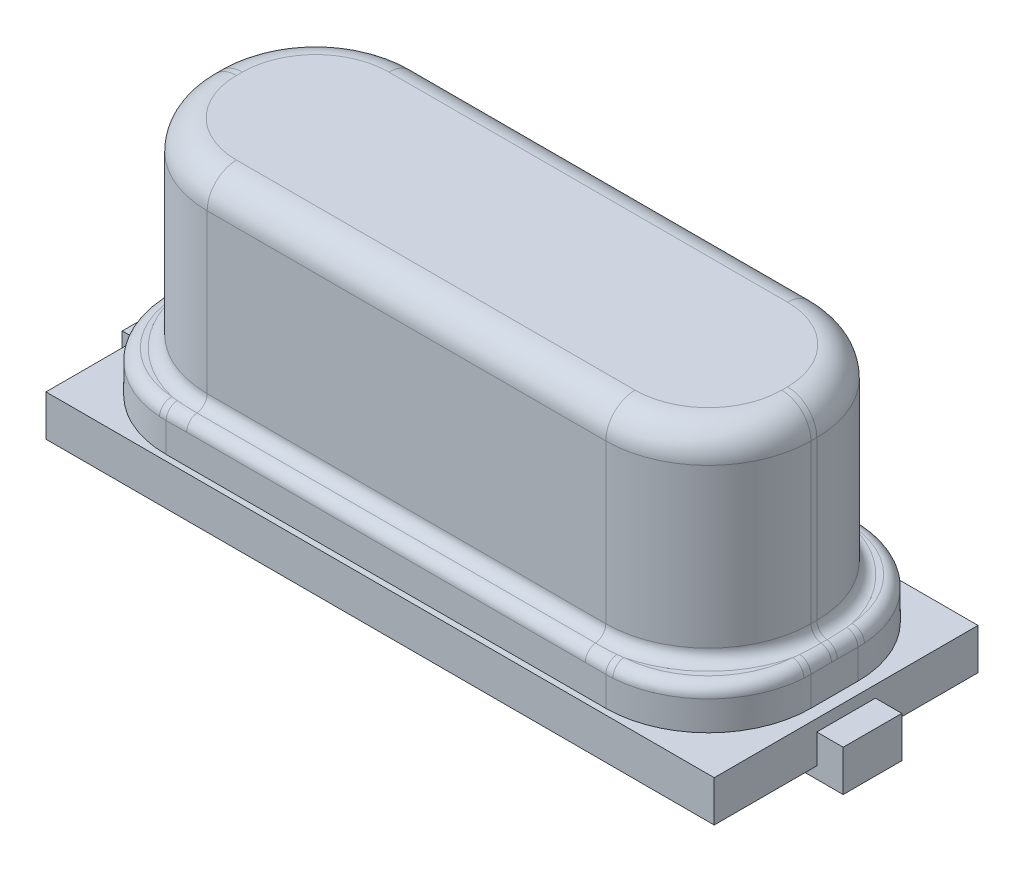
SolidWorks part; units mm, degrees
ref_plane "Спереди" through (0, 0, 0) normal (0, 0, 1) x (1, 0, 0)
ref_plane "Сверху" through (0, 0, 0) normal (0, 1, 0) x (1, 0, 0)
ref_plane "Справа" through (0, 0, 0) normal (1, 0, 0) x (0, 0, -1)
sketch "Эскиз1" plane through (0, 0, 0) normal (0, 1, 0) x (1, 0, 0)
  line L0 (-6.15, 0) -> (6.15, 0) construction
  line L1 (0, 2.25) -> (0, -2.25) construction
  line L2 (-6.15, 0.5) -> (-6.15, -0.5) construction
  line L4 (-6.15, 0.5) -> (-3, 0.5)
  line L5 (-6.15, 0.5) -> (-6.15, -0.5)
  line L6 (-6.15, -0.5) -> (-3, -0.5)
  line L7 (-3, 0.5) -> (-3, -0.5)
  line L8 (6.15, 0.5) -> (3, 0.5)
  line L9 (6.15, 0.5) -> (6.15, -0.5)
  line L10 (6.15, -0.5) -> (3, -0.5)
  line L11 (3, 0.5) -> (3, -0.5)
extrude "Бобышка-Вытянуть1" add sketch "Эскиз1" along normal blind 0.7
ref_plane "Плоскость1" through (0, 0.2, 0) normal (0, -1, 0) x (-1, 0, 0)
sketch "Эскиз6" plane through (0, 0.2, 0) normal (0, -1, 0) x (-1, 0, 0)
  line L1 (5.7, 2.25) -> (-5.7, 2.25)
  line L2 (5.7, 2.25) -> (5.7, -2.25)
  line L3 (5.7, -2.25) -> (-5.7, -2.25)
  line L4 (-5.7, 2.25) -> (-5.7, -2.25)
  line L5 (5.7, 2.25) -> (-5.7, -2.25) construction
  line L6 (5.7, -2.25) -> (-5.7, 2.25) construction
  point P0 (0, 0)
extrude "Бобышка-Вытянуть4" add sketch "Эскиз6" against normal blind 0.7
sketch "Эскиз7" plane through (0, 0.9, 0) normal (0, 1, 0) x (1, 0, 0)
  line L1 (-3.75, 2.15) -> (3.75, 2.15)
  line L2 (-5.5, 0.4) -> (-5.5, -0.4)
  line L3 (-3.75, -2.15) -> (3.75, -2.15)
  line L4 (5.5, 0.4) -> (5.5, -0.4)
  line L5 (-5.5, 2.15) -> (5.5, -2.15) construction
  line L6 (-5.5, -2.15) -> (5.5, 2.15) construction
  arc A0 (3.75, 2.15) -> (5.5, 0.4) centre (3.75, 0.4) cw
  arc A1 (3.75, -2.15) -> (5.5, -0.4) centre (3.75, -0.4) ccw
  arc A2 (-5.5, -0.4) -> (-3.75, -2.15) centre (-3.75, -0.4) ccw
  arc A3 (-3.75, 2.15) -> (-5.5, 0.4) centre (-3.75, 0.4) ccw
  point P0 (0, 0)
  dimension "D1" = 1.75
extrude "Бобышка-Вытянуть7" add sketch "Эскиз7" along normal blind 0.7
sketch "Эскиз9" plane through (0, 1.6, 0) normal (0, 1, 0) x (1, 0, 0)
  line L1 (3.4, -1.8) -> (-3.4, -1.8)
  line L2 (5.15, -0.05) -> (5.15, 0.05)
  line L3 (3.4, 1.8) -> (-3.4, 1.8)
  line L4 (-5.15, -0.05) -> (-5.15, 0.05)
  line L5 (5.15, -1.8) -> (-5.15, 1.8) construction
  line L6 (5.15, 1.8) -> (-5.15, -1.8) construction
  arc A0 (5.15, 0.05) -> (3.4, 1.8) centre (3.4, 0.05) ccw
  arc A1 (3.4, -1.8) -> (5.15, -0.05) centre (3.4, -0.05) ccw
  arc A2 (-3.4, -1.8) -> (-5.15, -0.05) centre (-3.4, -0.05) cw
  arc A3 (-3.4, 1.8) -> (-5.15, 0.05) centre (-3.4, 0.05) ccw
  point P0 (0, 0)
  dimension "D1" = 1.75
extrude "Бобышка-Вытянуть8" add sketch "Эскиз9" along normal blind 3.4
fillet "Скругление4" radius 0.5 8 edges at (-4.6374, 5, 1.2874) (-5.15, 5, 0) (-4.6374, 5, -1.2874) (0, 5, -1.8) (4.6374, 5, -1.2874) (5.15, 5, 0) (4.6374, 5, 1.2874) (0, 5, 1.8)
fillet "Скругление5" radius 0.2 8 edges at (-4.6374, 1.6, 1.2874) (-5.15, 1.6, 0) (-4.6374, 1.6, -1.2874) (0, 1.6, -1.8) (4.6374, 1.6, -1.2874) (5.15, 1.6, 0) (4.6374, 1.6, 1.2874) (0, 1.6, 1.8)
fillet "Скругление6" radius 0.2 8 edges at (-4.9874, 1.6, 1.6374) (-5.5, 1.6, 0) (-4.9874, 1.6, -1.6374) (0, 1.6, -2.15) (4.9874, 1.6, -1.6374) (5.5, 1.6, 0) (4.9874, 1.6, 1.6374) (0, 1.6, 2.15)
